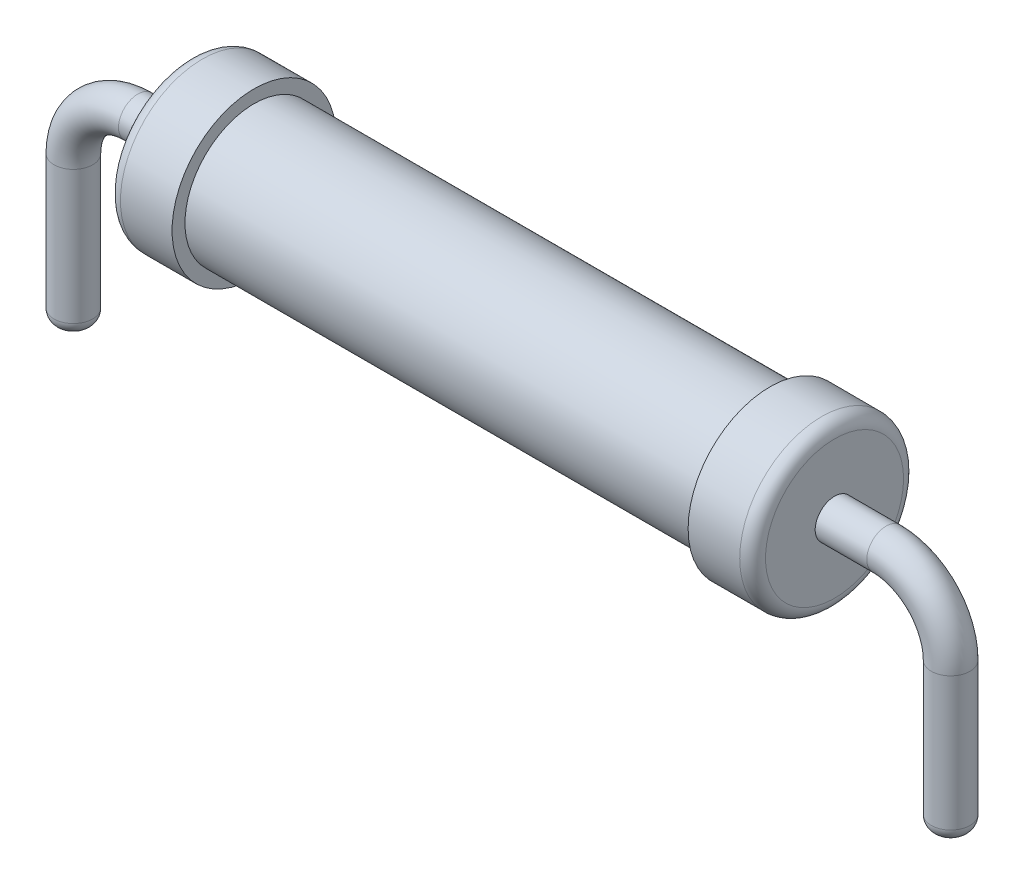
SolidWorks part; units mm, degrees
ref_plane "前视基准面" through (0, 0, 0) normal (0, 0, 1) x (1, 0, 0)
ref_plane "上视基准面" through (0, 0, 0) normal (0, 1, 0) x (1, 0, 0)
ref_plane "右视基准面" through (0, 0, 0) normal (1, 0, 0) x (0, 0, -1)
sketch "草图1" plane through (0, 0, 0) normal (1, 0, 0) x (0, 0, -1)
  circle A0 centre (0, 0) radius 1.27
  dimension "D1" = 2.54
extrude "凸台-拉伸1" add sketch "草图1" along normal mid plane 10
fillet "圆角1" radius 0.2 2 edges at (-5, 0, -1.27) (5, 0, -1.27)
sketch "草图2" plane through (5, 0, 0) normal (1, 0, 0) x (0, 0, -1)
  circle A0 centre (0, 0) radius 0.3
  dimension "D1" = 0.6
sketch "草图3" plane through (0, 0, 0) normal (0, 0, 1) x (1, 0, 0)
  line L0 (5, 0) -> (5.8, 0)
  line L1 (5, -0.3) -> (5, 0.3) construction
  line L2 (6.8, -1) -> (6.8, -3.27)
  line L3 (0, 0) -> (0, 4.8702) construction
  line L4 (-4.8, -1.27) -> (4.8, -1.27) construction
  arc A0 (6.8, -1) -> (5.8, 0) centre (5.8, -1) ccw
  dimension "D2" = 1
  dimension "D1" = 13.6
  dimension "D3" = 2
sweep "扫描1" add profiles "草图2" path "草图3"
fillet "圆角2" radius 0.2 1 edges at (6.8, -3.27, -0.3)
mirror "镜向1" about plane through (0, 0, 0) normal (1, 0, 0) of "圆角2", "扫描1"
sketch "草图4" plane through (0, 0, 0) normal (0, 1, 0) x (1, 0, 0)
  line L0 (0, -1.07) -> (0, -2.0511) construction
  line L1 (-4, -1.07) -> (4, -1.07)
  line L2 (-4, -1.07) -> (-4, -2.0511)
  line L4 (-4, -2.0511) -> (4, -2.0511)
  line L6 (-4.8, -1.27) -> (4.8, -1.27) construction
  line L7 (4, -1.07) -> (4, -2.0511)
  dimension "D1" = 0.2
  dimension "D2" = 8
ref_axis "基准轴1" through (7.81, 0, 0) along (-1, 0, 0)
sketch "草图6" plane through (0, 0, 0) normal (0, 1, 0) x (1, 0, 0)
  line L1 (-4, -1.07) -> (4, -1.07)
  line L2 (-4, -1.07) -> (-4, -2.0511)
  line L3 (-4, -2.0511) -> (4, -2.0511)
  line L4 (4, -1.07) -> (4, -2.0511)
revolve "切除-旋转2" cut sketch "草图6" angle 360 about axis through (7.81, 0, 0) along (-1, 0, 0)
